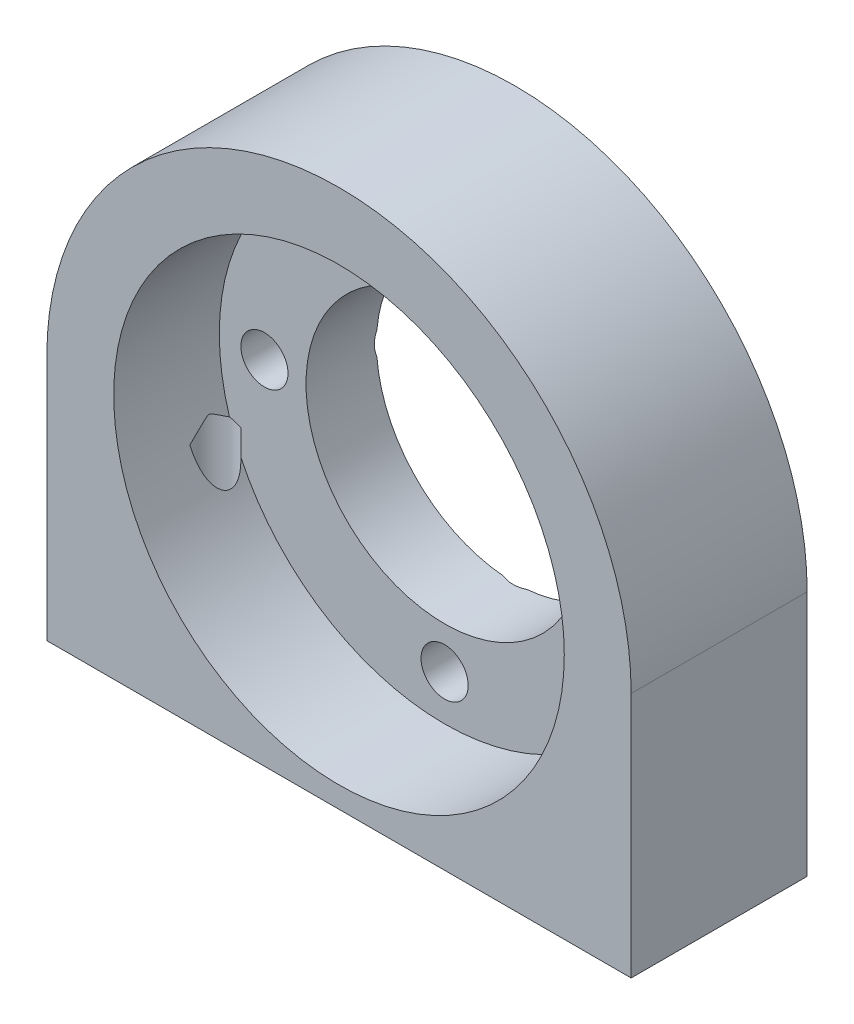
SolidWorks part; units mm, degrees
material "6061 Alloy"
ref_plane "Front Plane" through (0, 0, 0) normal (0, 0, 1) x (1, 0, 0)
ref_plane "Top Plane" through (0, 0, 0) normal (0, 1, 0) x (1, 0, 0)
ref_plane "Right Plane" through (0, 0, 0) normal (1, 0, 0) x (0, 0, -1)
sketch "Sketch1" plane through (0, 0, 0) normal (0, 0, 1) x (1, 0, 0)
  line L0 (-21.08, 0) -> (-21.08, -17.78)
  line L1 (-21.08, -17.78) -> (21.08, -17.78)
  line L2 (21.08, -17.78) -> (21.08, 0)
  circle A0 centre (0, 0) radius 16 construction
  arc A1 (21.08, 0) -> (-21.08, 0) centre (0, 0) ccw
  dimension "D1" = 32
  dimension "D2" = 5.08
  dimension "D3" = 17.78
extrude "Boss-Extrude1" add sketch "Sketch1" along normal mid plane 12.7
sketch "Sketch2" plane through (0, 0, 6.35) normal (0, 0, 1) x (1, 0, 0)
  circle A0 centre (0, 0) radius 16.256
  dimension "D1" = 32.512
extrude "Cut-Extrude1" cut sketch "Sketch2" against normal offset from surface (7.62 mm away) 5.08 up to face at (0, -3.62, -6.35)
sketch "Sketch3" plane through (0, 0, -1.27) normal (0, 0, 1) x (1, 0, 0)
  circle A0 centre (0, 0) radius 10
  dimension "D1" = 20
extrude "Cut-Extrude2" cut sketch "Sketch3" against normal through all
hole_wizard "CSK for M3 Flat Head Machine Screw1" positions "Sketch5" profile "Sketch6" countersink size "M3" standard "Ansi Metric" end condition through all
sketch "Sketch5" plane through (0, 0, -6.35) normal (0, 0, -1) x (-1, 0, 0)
  point P0 (0, 13)
  dimension "D1" = 13
sketch "Sketch6" plane through (0, 13, -6.35) normal (1, 0, 0) x (0, 1, 0)
  line L0 (0, 0) -> (0, 12.7)
  line L1 (0, 12.7) -> (1.7, 12.7)
  line L2 (1.7, 12.7) -> (1.7, 1.45)
  line L3 (1.7, 1.45) -> (3.15, 0)
  line L5 (3.15, 0) -> (0, 0)
  line L6 (-1.7, 1.45) -> (-3.15, 0) construction
  line L11 (0, -6.35) -> (0, 107.95) construction
  dimension "Thru Hole Dia." = 3.4
  dimension "Thru Hole Depth" = 12.7
  dimension "Near C'Sink Dia." = 6.3
  dimension "Near C'Sink Angle" = 90
pattern_circular "CirPattern1" count 4 over 360 about axis through (0, 0, 0) along (0, 0, 1) of "CSK for M3 Flat Head Machine Screw1"
hole_wizard "#8-32 Tapped Hole1" positions "Sketch8" profile "Sketch9" tap size "#8-32" standard "Ansi Inch"
sketch "Sketch8" plane through (0, -17.78, 0) normal (0, -1, 0) x (1, 0, 0)
  line L0 (-15.875, 0) -> (15.875, 0) construction
  point P0 (15.875, 0)
  point P7 (0, 0)
  point P9 (-15.875, 0)
  dimension "D1" = 31.75
sketch "Sketch9" plane through (15.875, -17.78, 0) normal (1, 0, 0) x (0, 0, -1)
  line L0 (0, 0) -> (0, 13.7378)
  line L1 (0, 13.7378) -> (1.7272, 12.7)
  line L2 (1.7272, 12.7) -> (1.7272, 0)
  line L5 (1.7272, 0) -> (0, 0)
  line L10 (0, 13.7378) -> (-1.7272, 12.7) construction
  line L11 (0, -6.35) -> (0, 107.95) construction
  dimension "Tap Drill Dia." = 3.4544
  dimension "Tap Drill Depth" = 12.7
  dimension "Drill Angle" = 118
